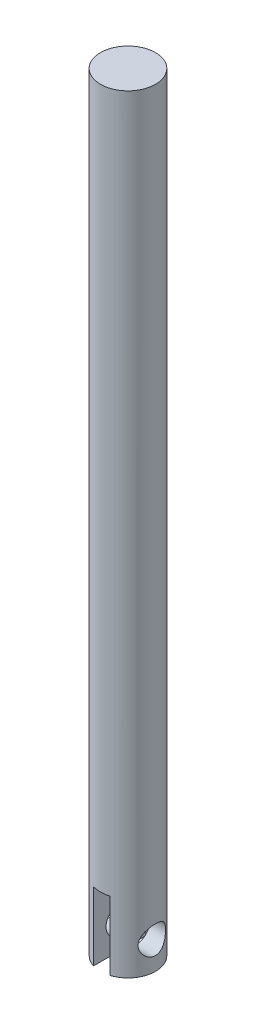
SolidWorks part; units mm, degrees
ref_plane "前视基准面" through (0, 0, 0) normal (0, 0, 1) x (1, 0, 0)
ref_plane "上视基准面" through (0, 0, 0) normal (0, 1, 0) x (1, 0, 0)
ref_plane "右视基准面" through (0, 0, 0) normal (1, 0, 0) x (0, 0, -1)
sketch "草图1" plane through (0, 0, 0) normal (0, 1, 0) x (1, 0, 0)
  circle A0 centre (0, 0) radius 2
  dimension "D1" = 4
extrude "凸台-拉伸1" add sketch "草图1" along normal blind 55.9
sketch "草图2" plane through (0, 0, 0) normal (0, 0, 1) x (1, 0, 0)
  line L1 (0.6, 5) -> (-0.6, 5)
  line L2 (0.6, 5) -> (0.6, -5)
  line L3 (0.6, -5) -> (-0.6, -5)
  line L4 (-0.6, 5) -> (-0.6, -5)
  line L5 (0.6, 5) -> (-0.6, -5) construction
  line L6 (0.6, -5) -> (-0.6, 5) construction
  point P0 (0, 0)
  dimension "D1" = 1.2
  dimension "D2" = 10
extrude "切除-拉伸1" cut sketch "草图2" against normal through all both and the other way through all
sketch "草图3" plane through (0, 0, 0) normal (1, 0, 0) x (0, 0, -1)
  line L0 (-1.9079, 0) -> (1.9079, 0) construction
  circle A0 centre (0, 2) radius 1
  dimension "D1" = 2
  dimension "D2" = 2
extrude "切除-拉伸2" cut sketch "草图3" against normal through all both and the other way through all
